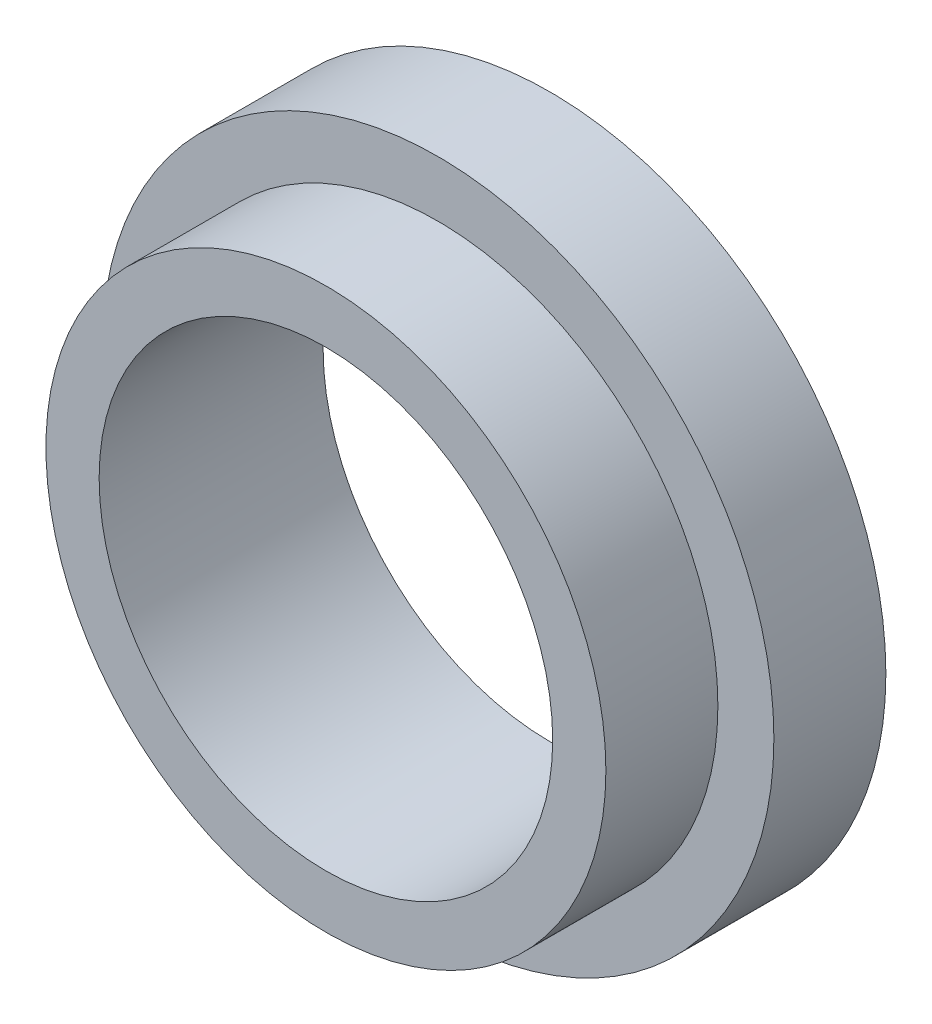
SolidWorks part; units mm, degrees
material "AISI 304"
ref_plane "Front" through (0, 0, 0) normal (0, 0, 1) x (1, 0, 0)
ref_plane "Top" through (0, 0, 0) normal (0, 1, 0) x (1, 0, 0)
ref_plane "Right" through (0, 0, 0) normal (1, 0, 0) x (0, 0, -1)
sketch "Sketch1" plane through (0, 0, 0) normal (1, 0, 0) x (0, 0, -1)
  line L0 (0, 4.05) -> (4, 4.05)
  line L1 (4, 4.05) -> (4, 6)
  line L2 (4, 6) -> (2, 6)
  line L3 (2, 6) -> (2, 5)
  line L4 (2, 5) -> (0, 5)
  line L5 (0, 5) -> (0, 4.05)
  line L6 (0, 0) -> (4, 0) construction
  dimension "D1" = 4
  dimension "D2" = 2
  dimension "D3" = 12
  dimension "D4" = 10
  dimension "D5" = 8.1
revolve "Revolve1" add sketch "Sketch1" angle 360 about L6
